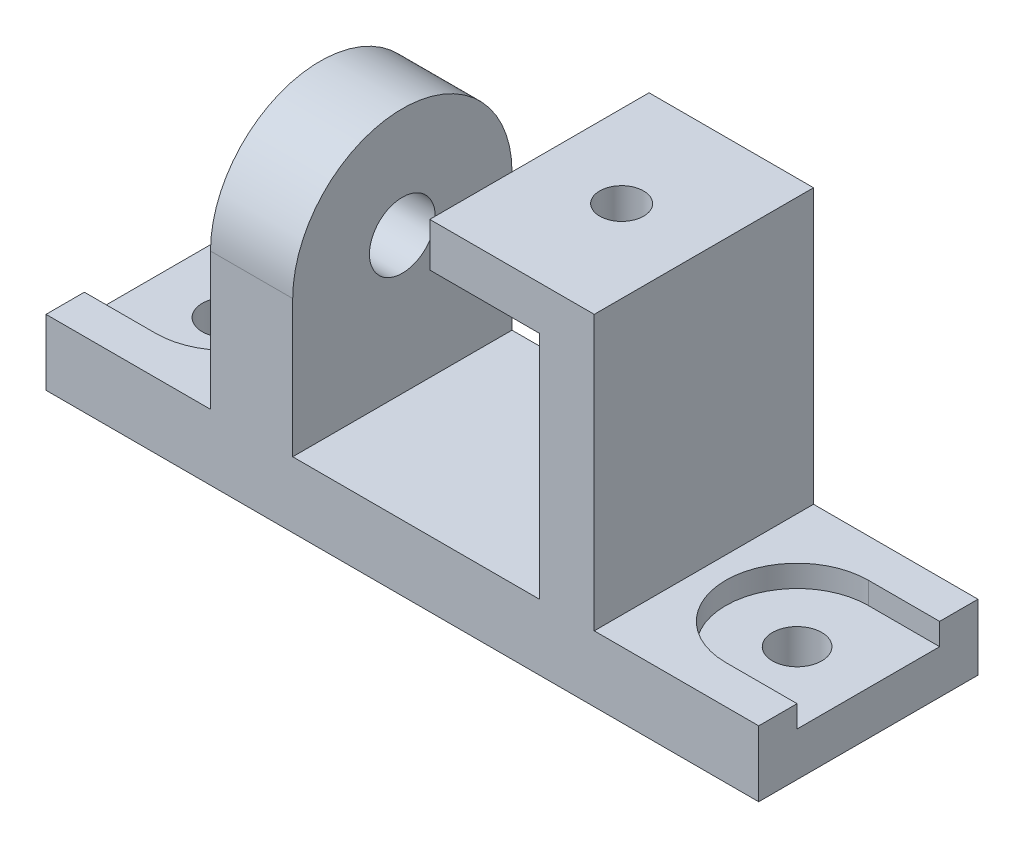
SolidWorks part; units mm, degrees
ref_plane "Plano frontal" through (0, 0, 0) normal (0, 0, 1) x (1, 0, 0)
ref_plane "Plano superior" through (0, 0, 0) normal (0, 1, 0) x (1, 0, 0)
ref_plane "Plano direito" through (0, 0, 0) normal (1, 0, 0) x (0, 0, -1)
sketch "Esboço1" plane through (0, 0, 0) normal (0, 1, 0) x (1, 0, 0)
  line L1 (-65, -20) -> (65, -20)
  line L2 (-65, -20) -> (-65, 20)
  line L3 (-65, 20) -> (65, 20)
  line L4 (65, -20) -> (65, 20)
  line L5 (-65, -20) -> (65, 20) construction
  line L6 (-65, 20) -> (65, -20) construction
  point P0 (0, 0)
  dimension "D1" = 40
  dimension "D2" = 130
extrude "Ressalto-extrusão1" add sketch "Esboço1" along normal blind 12
sketch "Esboço3" plane through (0, 12, 0) normal (0, 1, 0) x (1, 0, 0)
  line L0 (65, 13) -> (52, 13)
  line L1 (-65, 20) -> (-65, -20) construction
  line L2 (65, -20) -> (65, 20) construction
  line L3 (-65, 13) -> (-52, 13)
  line L4 (-65, -13) -> (-52, -13)
  line L5 (65, -13) -> (52, -13)
  arc A0 (-52, -13) -> (-52, 13) centre (-52, 0) ccw
  arc A1 (52, 13) -> (52, -13) centre (52, 0) ccw
  dimension "D1" = 13
  dimension "D2" = 13
  dimension "D3" = 26
  dimension "D4" = 13
  dimension "D5" = 13
extrude "Corte-extrusão3" cut sketch "Esboço3" against normal blind 4 and the other way through all contours L4 A0 L3
sketch "Esboço4" plane through (0, 12, 0) normal (0, 1, 0) x (1, 0, 0)
  line L0 (65, 13) -> (52, 13)
  line L1 (65, -20) -> (65, 20) construction
  line L2 (52, -13) -> (65, -13)
  arc A0 (52, 13) -> (52, -13) centre (52, 0) ccw
  dimension "D1" = 13
  dimension "D2" = 13
extrude "Corte-extrusão4" cut sketch "Esboço4" against normal blind 4 and the other way through all
sketch "Esboço5" plane through (0, 8, 0) normal (0, 1, 0) x (1, 0, 0)
  circle A0 centre (-52, 0) radius 4.5
  circle A1 centre (52, 0) radius 4.5
  dimension "D1" = 9
  dimension "D2" = 9
extrude "Corte-extrusão5" cut sketch "Esboço5" against normal through all
sketch "Esboço7" plane through (0, 12, 0) normal (0, 1, 0) x (1, 0, 0)
  line L0 (-35, 20) -> (-20, 20)
  line L1 (65, 20) -> (-65, 20) construction
  line L2 (-35, 20) -> (-35, -20)
  line L3 (-65, -20) -> (65, -20) construction
  line L4 (-35, -20) -> (-20, -20)
  line L14 (-20, 20) -> (-20, -20)
  dimension "D1" = 15
extrude "Ressalto-extrusão2" add sketch "Esboço7" along normal blind 50 contours L14 L4 L2 L0
sketch "Esboço8" plane through (0, 12, 0) normal (0, 1, 0) x (1, 0, 0)
  line L1 (65, 20) -> (-20, 20) construction
  line L2 (25, 20) -> (35, 20)
  line L3 (35, 20) -> (35, -20)
  line L4 (-20, -20) -> (65, -20) construction
  line L5 (35, -20) -> (25, -20)
  line L6 (25, -20) -> (25, 20)
  dimension "D1" = 10
extrude "Ressalto-extrusão3" add sketch "Esboço8" along normal blind 50
sketch "Esboço9" plane through (25, 0, 0) normal (-1, 0, 0) x (0, 0, 1)
  line L0 (-20, 62) -> (-20, 54)
  line L1 (-20, 62) -> (-20, 12) construction
  line L2 (-20, 54) -> (20, 54)
  line L3 (20, 62) -> (20, 12) construction
  line L4 (20, 54) -> (20, 62)
  line L5 (20, 62) -> (-20, 62)
  dimension "D1" = 8
extrude "Ressalto-extrusão4" add sketch "Esboço9" along normal blind 20
sketch "Esboço10" plane through (0, 62, 0) normal (0, 1, 0) x (1, 0, 0)
  circle A0 centre (20, 0) radius 4
  dimension "D1" = 8
extrude "Corte-extrusão6" cut sketch "Esboço10" against normal blind 20
sketch "Esboço11" plane through (-35, 0, 0) normal (-1, 0, 0) x (0, 0, 1)
  line L0 (-20, 37) -> (-20, 62)
  line L1 (-20, 62) -> (20, 62)
  line L2 (20, 62) -> (20, 37)
  arc A0 (20, 37) -> (-20, 37) centre (0, 37) ccw
  circle A1 centre (0, 37) radius 6
  dimension "D1" = 12
  dimension "D2" = 20
  dimension "D3" = 40
extrude "Corte-extrusão7" cut sketch "Esboço11" against normal blind 20 contours A0 L0 L1 L2
sketch "Esboço12" plane through (-35, 0, 0) normal (-1, 0, 0) x (0, 0, 1)
  circle A0 centre (0, 37) radius 6
  dimension "D1" = 12
extrude "Corte-extrusão8" cut sketch "Esboço12" against normal blind 20
